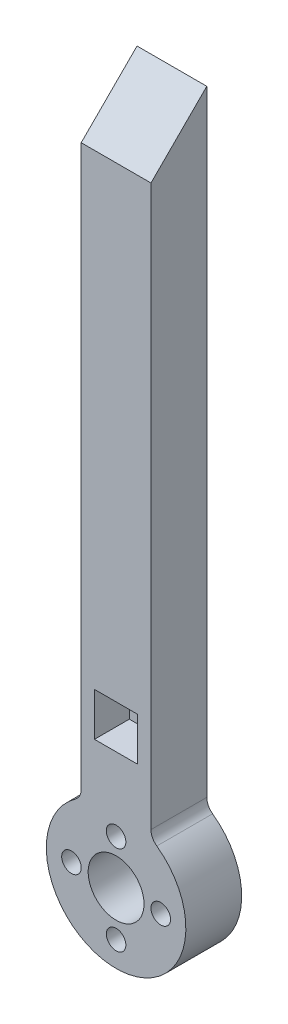
SolidWorks part; units mm, degrees
ref_plane "Front Plane" through (0, 0, 0) normal (0, 0, 1) x (1, 0, 0)
ref_plane "Top Plane" through (0, 0, 0) normal (0, 1, 0) x (1, 0, 0)
ref_plane "Right Plane" through (0, 0, 0) normal (1, 0, 0) x (0, 0, -1)
sketch "Sketch1" plane through (0, 0, 0) normal (0, 0, 1) x (1, 0, 0)
  line L0 (0, 0) -> (0, 127) construction
  line L1 (-6.35, 12.7) -> (-6.35, 10.9985)
  line L2 (-6.35, 12.7) -> (-8.2139, 12.7)
  line L3 (6.35, 12.7) -> (6.35, 10.9985)
  line L5 (-6.35, 12.7) -> (-6.35, 114.3)
  line L6 (-6.35, 114.3) -> (6.35, 114.3)
  line L7 (6.35, 12.7) -> (6.35, 114.3)
  circle A0 centre (0, 0) radius 5.08
  arc A1 (-6.35, 10.9985) -> (6.35, 10.9985) centre (0, 0) ccw
  circle A2 centre (0, 8.128) radius 1.778
  circle A3 centre (8.128, 0) radius 1.778
  circle A4 centre (0, -8.128) radius 1.778
  circle A5 centre (-8.128, 0) radius 1.778
  point P15 (0, 0)
  dimension "D1" = 10.16
  dimension "D2" = 25.4
  dimension "D4" = 3.556
  dimension "D3" = 8.128
  dimension "D6" = 12.7
  dimension "D7" = 101.6
  dimension "D5" = 4
extrude "Boss-Extrude1" add sketch "Sketch1" along normal blind 10.16
sketch "Sketch2" plane through (6.35, 0, 0) normal (-1, 0, 0) x (0, 0, 1)
  line L0 (0, 124.46) -> (10.16, 114.3)
  line L1 (10.16, 114.3) -> (0, 114.3)
  line L4 (0, 114.3) -> (0, 124.46)
  dimension "D1" = 10.16
  dimension "D2" = 14.3684
extrude "Boss-Extrude3" add sketch "Sketch2" along normal up to surface (12.7 mm away) up to face at (-6.35, 62.6493, 5.08)
sketch "Sketch3" plane through (0, 0, 10.16) normal (0, 0, 1) x (1, 0, 0)
  line L0 (0, 0) -> (0, 25.4) construction
  line L2 (-3.937, 21.463) -> (3.937, 21.463)
  line L3 (-3.937, 21.463) -> (-3.937, 29.337)
  line L4 (-3.937, 29.337) -> (3.937, 29.337)
  line L5 (3.937, 21.463) -> (3.937, 29.337)
  line L6 (-3.937, 21.463) -> (3.937, 29.337) construction
  line L7 (-3.937, 29.337) -> (3.937, 21.463) construction
  dimension "D1" = 7.874
  dimension "D2" = 7.874
  dimension "D3" = 25.4
extrude "Cut-Extrude1" cut sketch "Sketch3" against normal blind 6.35
fillet "Fillet1" radius 2.54 2 edges at (6.35, 10.9985, 5.08) (-6.35, 10.9985, 5.08)
